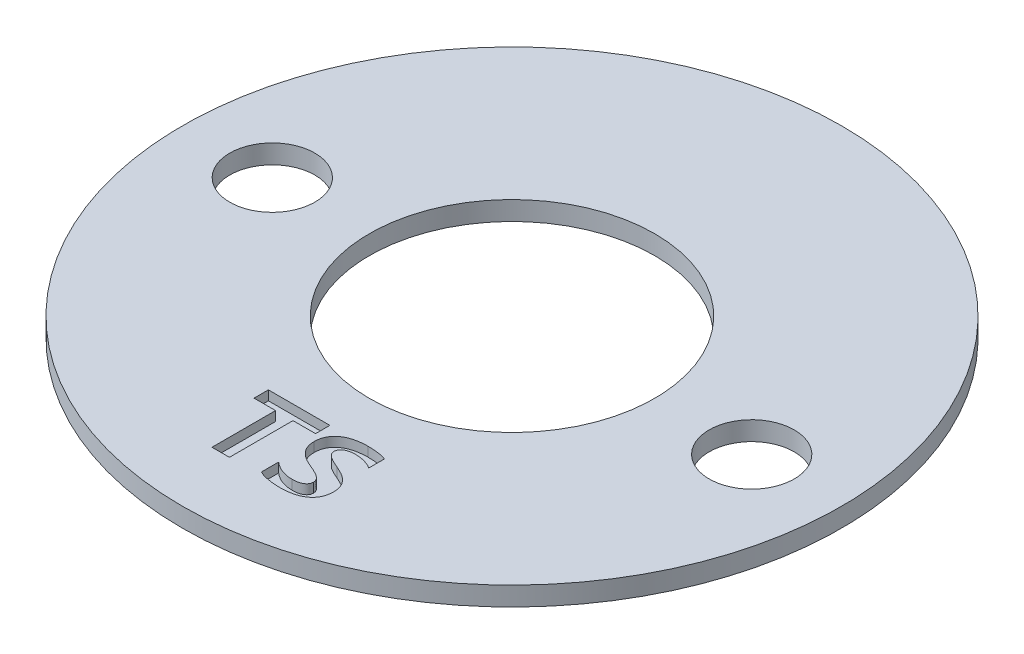
SolidWorks part; units mm, degrees
material "ABS"
ref_plane "Front Plane" through (0, 0, 0) normal (0, 0, 1) x (1, 0, 0)
ref_plane "Top Plane" through (0, 0, 0) normal (0, 1, 0) x (1, 0, 0)
ref_plane "Right Plane" through (0, 0, 0) normal (1, 0, 0) x (0, 0, -1)
sketch "Sketch1" plane through (0, 0, 0) normal (0, 1, 0) x (1, 0, 0)
  circle A0 centre (0, 0) radius 27.5
  dimension "D1" = 55
extrude "Boss-Extrude1" add sketch "Sketch1" along normal blind 1.5875
sketch "Sketch4" plane through (0, 0, 0) normal (0, -1, 0) x (1, 0, 0)
  line L0 (-20.0025, 0) -> (20.0025, 0) construction
  circle A4 centre (-20.0025, 0) radius 3.55
  circle A5 centre (0, 0) radius 11.9062
  circle A6 centre (20.0025, 0) radius 3.55
  dimension "D1" = 7.1
  dimension "D2" = 23.8125
  dimension "D3" = 40.005
extrude "Cut-Extrude2" cut sketch "Sketch4" against normal through all
sketch "Sketch2" plane through (0, 1.5875, 0) normal (0, 1, 0) x (1, 0, 0)
  line L0 (-5, -22) -> (5, -22) construction
  line L1 (0, 0) -> (0, -22) construction
  text T0 "TS" font "Nirmala UI" height 6.5
  dimension "D1" = 10
  dimension "D2" = 22
extrude "Cut-Extrude1" cut sketch "Sketch2" against normal offset from surface (0.7938 mm away) 0.7937 up to face at (-20.0025, 0, -3.55)
